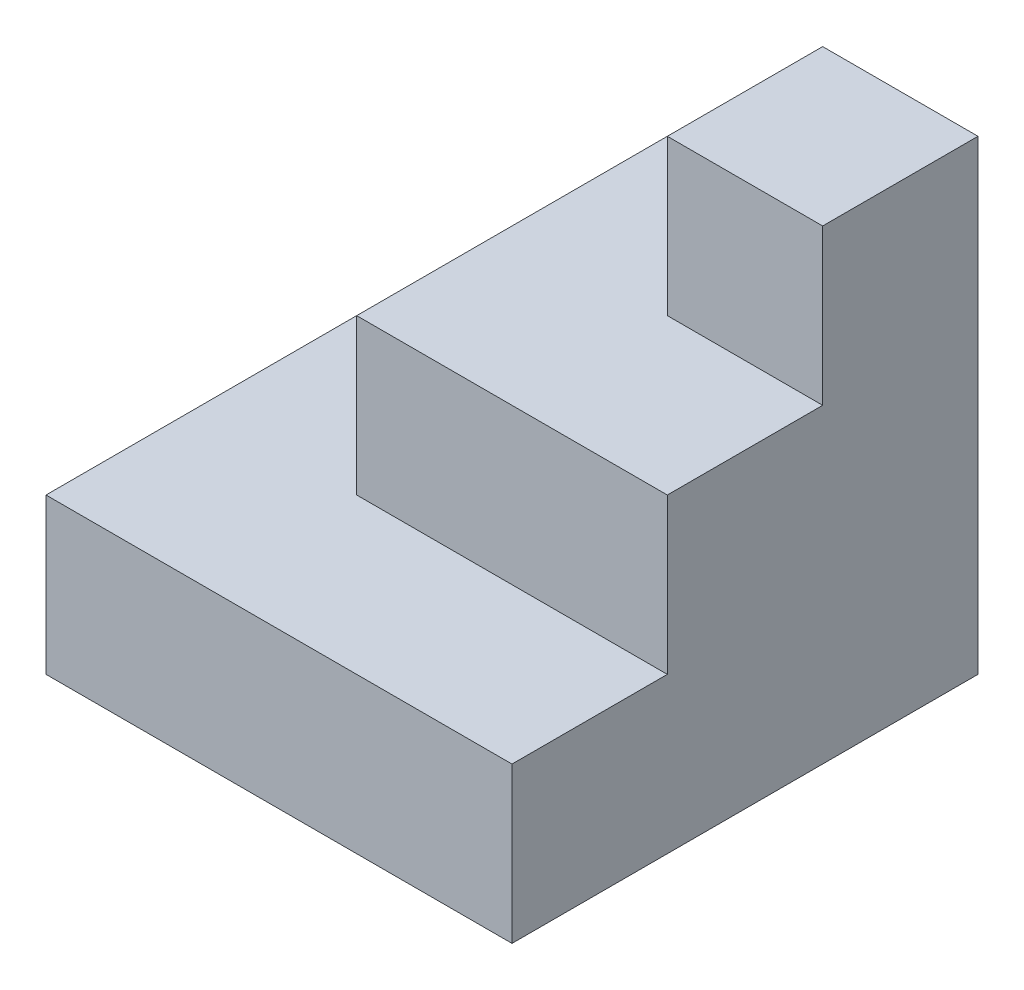
SolidWorks part; units mm, degrees
ref_plane "Front Plane" through (0, 0, 0) normal (0, 0, 1) x (1, 0, 0)
ref_plane "Top Plane" through (0, 0, 0) normal (0, 1, 0) x (1, 0, 0)
ref_plane "Right Plane" through (0, 0, 0) normal (1, 0, 0) x (0, 0, -1)
sketch "Sketch1" plane through (0, 0, 0) normal (0, 0, 1) x (1, 0, 0)
  line L0 (0, 0) -> (0, 15)
  line L1 (0, 15) -> (-5, 15)
  line L2 (-5, 15) -> (-5, 10)
  line L3 (-5, 10) -> (-10, 10)
  line L4 (-10, 10) -> (-10, 5)
  line L5 (-10, 5) -> (-15, 5)
  line L6 (-15, 5) -> (-15, 0)
  line L7 (-15, 0) -> (0, 0)
  dimension "D1" = 15
  dimension "D2" = 15
  dimension "D3" = 5
  dimension "D4" = 5
  dimension "D5" = 5
  dimension "D6" = 5
extrude "Boss-Extrude1" add sketch "Sketch1" along normal blind 15
sketch "Sketch2" plane through (0, 0, 15) normal (0, 0, 1) x (1, 0, 0)
  line L0 (-10, 5) -> (0, 5)
  line L1 (0, 0) -> (0, 15) construction
  line L2 (-10, 10) -> (0, 10)
  line L3 (-10, 10) -> (-10, 5)
  line L4 (0, 10) -> (0, 5)
extrude "Cut-Extrude1" cut sketch "Sketch2" against normal blind 5
sketch "Sketch3" plane through (0, 0, 15) normal (0, 0, 1) x (1, 0, 0)
  line L4 (-5, 10) -> (0, 10)
  line L5 (0, 10) -> (0, 15)
  line L6 (0, 15) -> (-5, 15)
  line L7 (-5, 15) -> (-5, 10)
  line L8 (-5, 10) -> (0, 10)
  line L9 (0, 10) -> (0, 15)
  line L10 (0, 15) -> (-5, 15)
  line L11 (-5, 15) -> (-5, 10)
  dimension "D1" = 0
extrude "Cut-Extrude2" cut sketch "Sketch3" against normal blind 10
